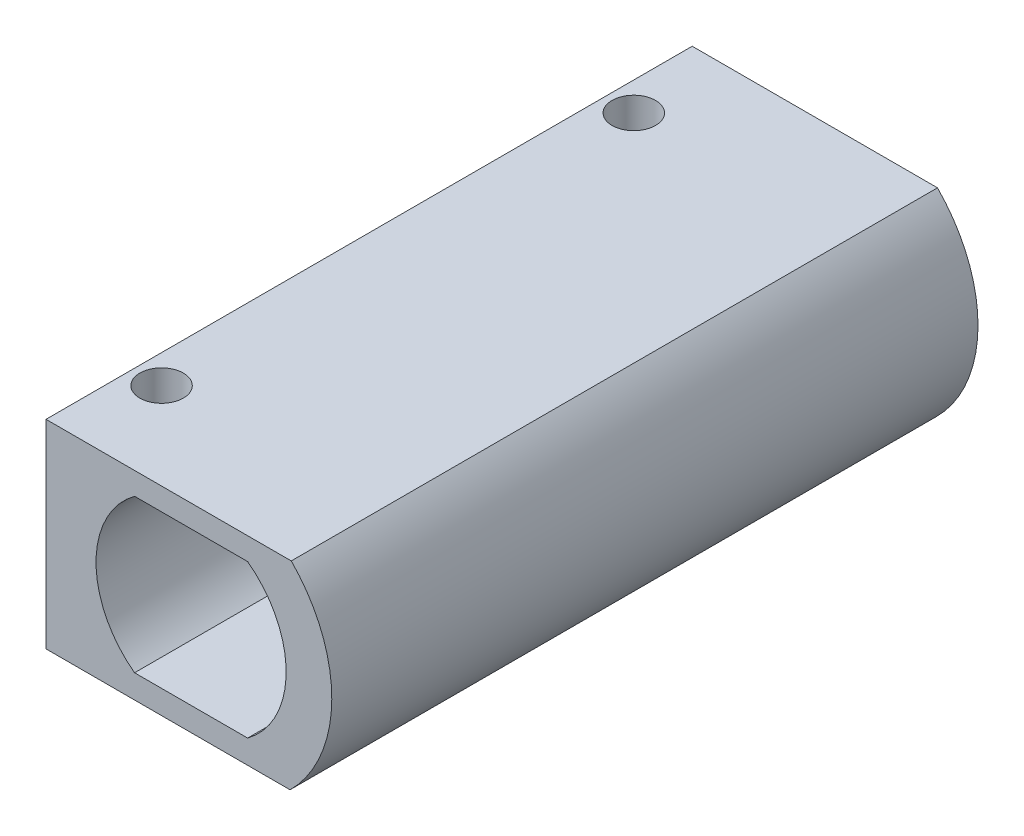
SolidWorks part; units mm, degrees
ref_plane "Alzado" through (0, 0, 0) normal (0, 0, 1) x (1, 0, 0)
ref_plane "Planta" through (0, 0, 0) normal (0, 1, 0) x (1, 0, 0)
ref_plane "Vista lateral" through (0, 0, 0) normal (1, 0, 0) x (0, 0, -1)
sketch "Croquis1" plane through (0, 0, 0) normal (0, 0, 1) x (1, 0, 0)
  line L1 (-22.1523, 15.7088) -> (-3.0323, 15.7088)
  line L2 (-22.1523, 15.7088) -> (-22.1523, -0.2912)
  line L3 (-22.1523, -0.2912) -> (-3.0323, -0.2912)
  line L4 (-3.0323, -0.1912) -> (-3.0323, -0.2912)
  line L5 (-6.5425, 13.9088) -> (-15.642, 13.9088)
  line L7 (-6.5425, 1.6088) -> (-15.642, 1.6088)
  arc A0 (-6.5425, 1.6088) -> (-6.5425, 13.9088) centre (-11.0923, 7.7588) ccw
  arc A1 (-15.642, 13.9088) -> (-15.642, 1.6088) centre (-11.0923, 7.7588) ccw
  arc A2 (-3.1321, -0.2912) -> (-3.0323, 15.7088) centre (-11.0923, 7.7588) ccw
  point P10 (-12.5923, -0.2912)
  dimension "D3" = 15.3
  dimension "D1" = 19.12
  dimension "D2" = 16
  dimension "D6" = 1.5
  dimension "D7" = 1.9
extrude "Saliente-Extruir1" add sketch "Croquis1" along normal blind 52 contours L3 A2 L1 L2 A1 L5 A0 L7
sketch "Croquis3" plane through (0, 0, 52) normal (0, 0, 1) x (1, 0, 0)
  line L1 (-22.1523, 15.7088) -> (-22.7679, 15.7088)
  line L2 (-22.1523, 15.7088) -> (-22.1523, -0.2912)
  line L3 (-22.1523, -0.2912) -> (-22.7679, -0.2912)
  line L4 (-22.7679, 15.7088) -> (-22.7679, -0.2912)
extrude "Saliente-Extruir2" add sketch "Croquis3" against normal blind 52
sketch "Croquis2" plane through (0, 15.7088, 0) normal (0, 1, 0) x (1, 0, 0)
  line L4 (-22.7679, -52) -> (-3.0323, -52) construction
  line L5 (-22.7679, 0) -> (-3.0323, 0) construction
  circle A0 centre (-20.4679, -7) radius 1.75
  circle A1 centre (-20.4679, -45) radius 1.75
  dimension "D1" = 3.5
  dimension "D2" = 3.5
  dimension "D3" = 2.3
  dimension "D4" = 2.3
  dimension "D5" = 7
  dimension "D6" = 7
  dimension "D7" = 38
extrude "Cortar-Extruir1" cut sketch "Croquis2" against normal blind 52
sketch "Croquis4" plane through (-22.7679, 0, 0) normal (-1, 0, 0) x (0, 0, 1)
  line L1 (29.4455, 3.7558) -> (22.5545, 3.7558)
  line L2 (29.4455, 3.7558) -> (29.4455, 11.6618)
  line L3 (29.4455, 11.6618) -> (22.5545, 11.6618)
  line L4 (22.5545, 3.7558) -> (22.5545, 11.6618)
  line L5 (29.4455, 3.7558) -> (22.5545, 11.6618) construction
  line L6 (29.4455, 11.6618) -> (22.5545, 3.7558) construction
  point P0 (26, 7.7088)
extrude "Cortar-Extruir2" cut sketch "Croquis4" against normal blind 10
